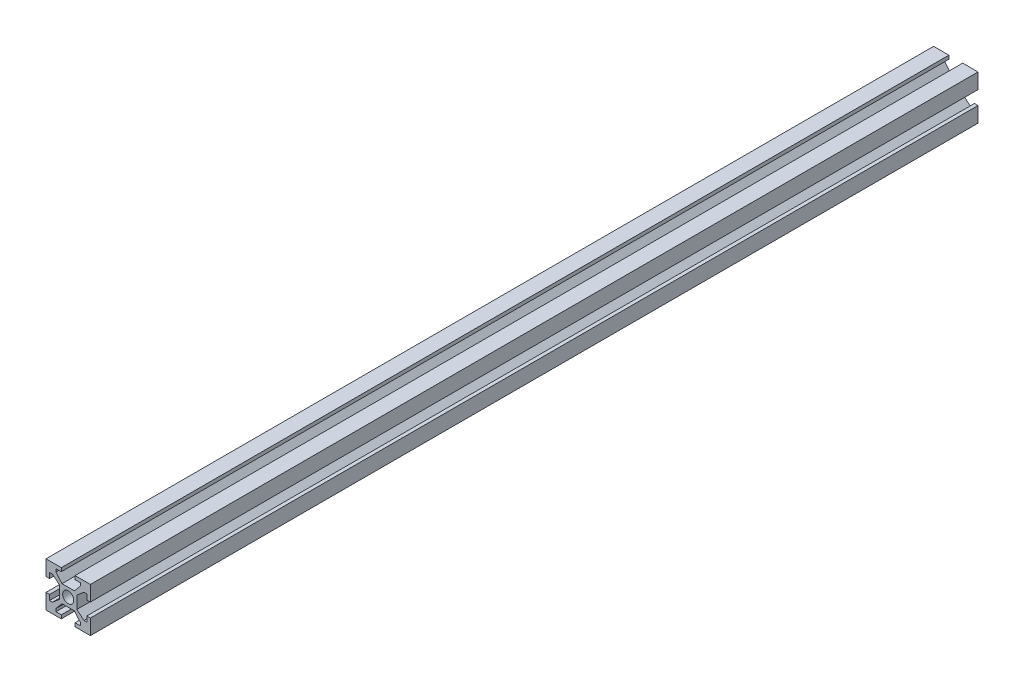
SolidWorks part; units mm, degrees
ref_plane "前视基准面" through (0, 0, 0) normal (0, 0, 1) x (1, 0, 0)
ref_plane "上视基准面" through (0, 0, 0) normal (0, 1, 0) x (1, 0, 0)
ref_plane "右视基准面" through (0, 0, 0) normal (1, 0, 0) x (0, 0, -1)
sketch "草图1" plane through (0, 0, 0) normal (0, 0, 1) x (1, 0, 0)
  line L0 (-10, 20) -> (-10, 0) construction
  line L1 (-20, 20) -> (-13.1, 20)
  line L2 (-20, 20) -> (-20, 13.1)
  line L3 (-20, 0) -> (-13.1, 0)
  line L4 (0, 20) -> (0, 13.1)
  line L5 (-20, 10) -> (0, 10) construction
  line L6 (-13.1, 20) -> (-13.1, 18.4)
  line L7 (-13.1, 18.4) -> (-15.5, 18.4)
  line L8 (-15.5, 18.4) -> (-15.5, 17.1043)
  line L9 (-15.5, 17.1043) -> (-12.797, 13.9)
  line L10 (-12.797, 13.9) -> (-7.203, 13.9)
  line L11 (-4.5, 17.1043) -> (-7.203, 13.9)
  line L12 (-4.5, 18.4) -> (-4.5, 17.1043)
  line L13 (-6.9, 20) -> (-6.9, 18.4)
  line L14 (-6.9, 18.4) -> (-4.5, 18.4)
  line L15 (-1.6, 13.1) -> (-1.6, 15.5)
  line L16 (-1.6, 15.5) -> (-2.8957, 15.5)
  line L17 (-2.8957, 15.5) -> (-6.1, 12.797)
  line L18 (-6.1, 12.797) -> (-6.1, 7.203)
  line L19 (-2.8957, 4.5) -> (-6.1, 7.203)
  line L20 (-1.6, 4.5) -> (-2.8957, 4.5)
  line L21 (-1.6, 6.9) -> (-1.6, 4.5)
  line L22 (0, 6.9) -> (-1.6, 6.9)
  line L23 (0, 13.1) -> (-1.6, 13.1)
  line L24 (-6.9, 1.6) -> (-4.5, 1.6)
  line L25 (-4.5, 1.6) -> (-4.5, 2.8957)
  line L26 (-4.5, 2.8957) -> (-7.203, 6.1)
  line L27 (-7.203, 6.1) -> (-12.797, 6.1)
  line L28 (-15.5, 2.8957) -> (-12.797, 6.1)
  line L29 (-15.5, 1.6) -> (-15.5, 2.8957)
  line L30 (-13.1, 1.6) -> (-15.5, 1.6)
  line L31 (-13.1, 0) -> (-13.1, 1.6)
  line L32 (-6.9, 0) -> (-6.9, 1.6)
  line L33 (-18.4, 6.9) -> (-18.4, 4.5)
  line L34 (-18.4, 4.5) -> (-17.1043, 4.5)
  line L35 (-17.1043, 4.5) -> (-13.9, 7.203)
  line L36 (-13.9, 7.203) -> (-13.9, 12.797)
  line L37 (-17.1043, 15.5) -> (-13.9, 12.797)
  line L38 (-18.4, 15.5) -> (-17.1043, 15.5)
  line L39 (-18.4, 13.1) -> (-18.4, 15.5)
  line L40 (-20, 13.1) -> (-18.4, 13.1)
  line L41 (-20, 6.9) -> (-18.4, 6.9)
  line L42 (-6.9, 20) -> (0, 20)
  line L43 (0, 6.9) -> (0, 0)
  line L44 (-20, 6.9) -> (-20, 0)
  line L45 (-6.9, 0) -> (0, 0)
  circle A0 centre (-10, 10) radius 2.5
  point P18 (-10, 13.9)
  point P55 (-10, 10)
  dimension "D3" = 5
  dimension "D1" = 20
  dimension "D2" = 20
  dimension "D4" = 5.5
  dimension "D5" = 6.1
  dimension "D6" = 3.1
  dimension "D7" = 1.6
  dimension "D8" = 4
extrude "凸台-拉伸1" add sketch "草图1" along normal blind 400
